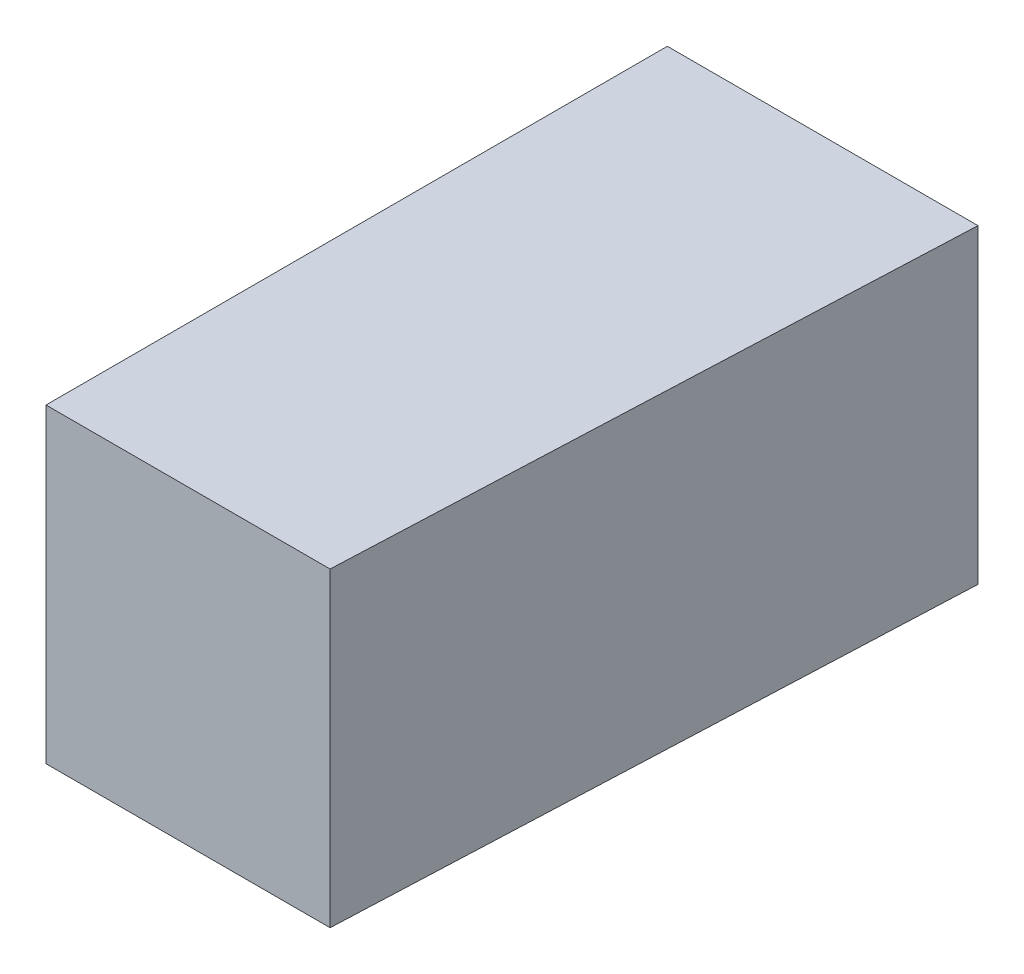
SolidWorks part; units mm, degrees
ref_plane "Front" through (0, 0, 0) normal (0, 0, 1) x (1, 0, 0)
ref_plane "Top" through (0, 0, 0) normal (0, 1, 0) x (1, 0, 0)
ref_plane "Right" through (0, 0, 0) normal (1, 0, 0) x (0, 0, -1)
sketch "Sketch4" plane through (0, 0, 0) normal (0, 1, 0) x (1, 0, 0)
  line L1 (0, 0) -> (10, 0)
  line L2 (0, 0) -> (0, 20)
  line L3 (0, 20) -> (10, 20)
  line L4 (10, 0) -> (10, 20)
  dimension "D1" = 20
  dimension "D2" = 10
extrude "Boss-Extrude1" add sketch "Sketch4" along normal blind 10
sketch "Sketch2" plane through (0, 0, 0) normal (0, -1, 0) x (-1, 0, 0)
  line L0 (-10, 10) -> (0, 10) construction
  line L1 (-10, 0) -> (-10, 20) construction
  line L2 (0, 20) -> (0, 0) construction
  line L3 (0, 6.615) -> (-1.8, 6.615)
  line L4 (-1.8, 6.615) -> (-1.8, 4.5)
  line L5 (-1.8, 4.5) -> (-3.44, 4.5)
  line L6 (-3.44, 4.5) -> (-6.1, 7.16)
  line L7 (-6.1, 7.16) -> (-6.1, 12.84)
  line L16 (-6.1, 12.84) -> (-3.44, 15.5)
  line L17 (-3.44, 15.5) -> (-1.8, 15.5)
  line L18 (-1.8, 15.5) -> (-1.8, 13.385)
  line L19 (-1.8, 13.385) -> (0, 13.385)
  line L20 (0, 13.385) -> (0, 6.615)
  dimension "D1" = 11
  dimension "D2" = 1.64
  dimension "D3" = 4.3
  dimension "D4" = 1.8
  dimension "D9" = 6.77
extrude "Cut-Extrude1" cut sketch "Sketch2" against normal blind 8
sketch "Sketch6" plane through (0, 0, 0) normal (0, -1, 0) x (1, 0, 0)
  line L0 (10, 0) -> (9.1443, 0)
  line L2 (0, 0) -> (10, 0) construction
  line L3 (10, -20) -> (10, 0)
  line L5 (9.1443, 0) -> (10, -20)
  line L6 (10, -20) -> (0, -20) construction
  dimension "D1" = 87.55
extrude "Cut-Extrude2" cut sketch "Sketch6" against normal through all
